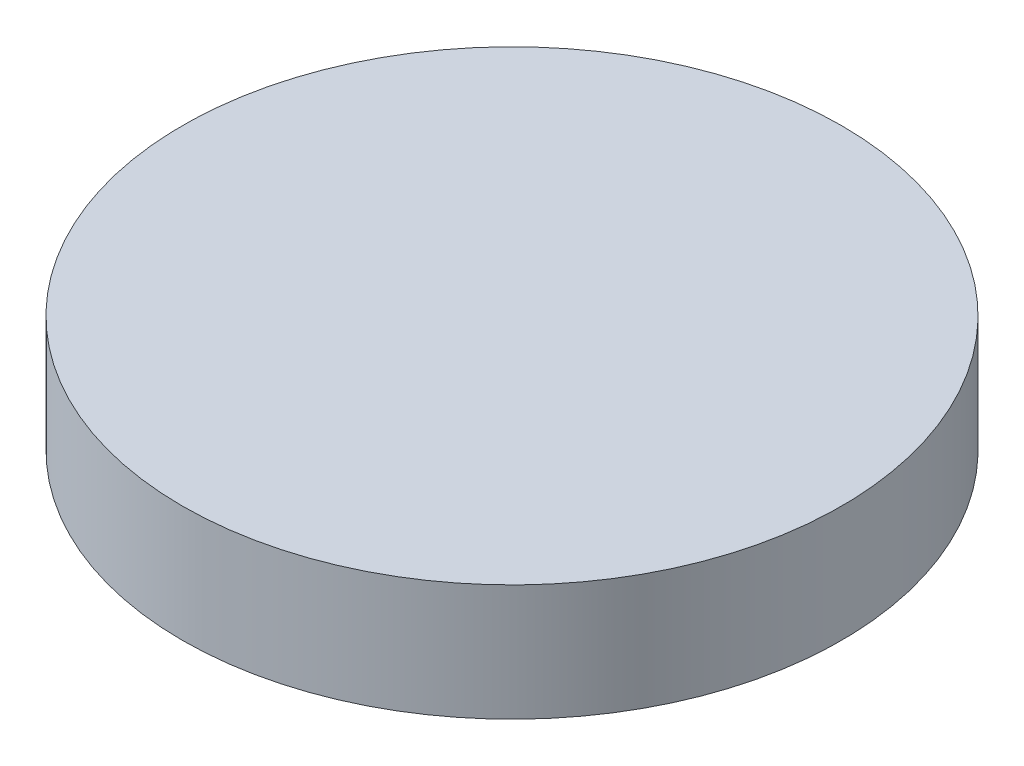
SolidWorks part; units mm, degrees
ref_plane "Front Plane" through (0, 0, 0) normal (0, 0, 1) x (1, 0, 0)
ref_plane "Top Plane" through (0, 0, 0) normal (0, 1, 0) x (1, 0, 0)
ref_plane "Right Plane" through (0, 0, 0) normal (1, 0, 0) x (0, 0, -1)
sketch "Sketch2" plane through (0, 0, 0) normal (0, 1, 0) x (1, 0, 0)
  circle A0 centre (0, 0) radius 17
  dimension "D1" = 34
extrude "Boss-Extrude1" add sketch "Sketch2" along normal blind 6
